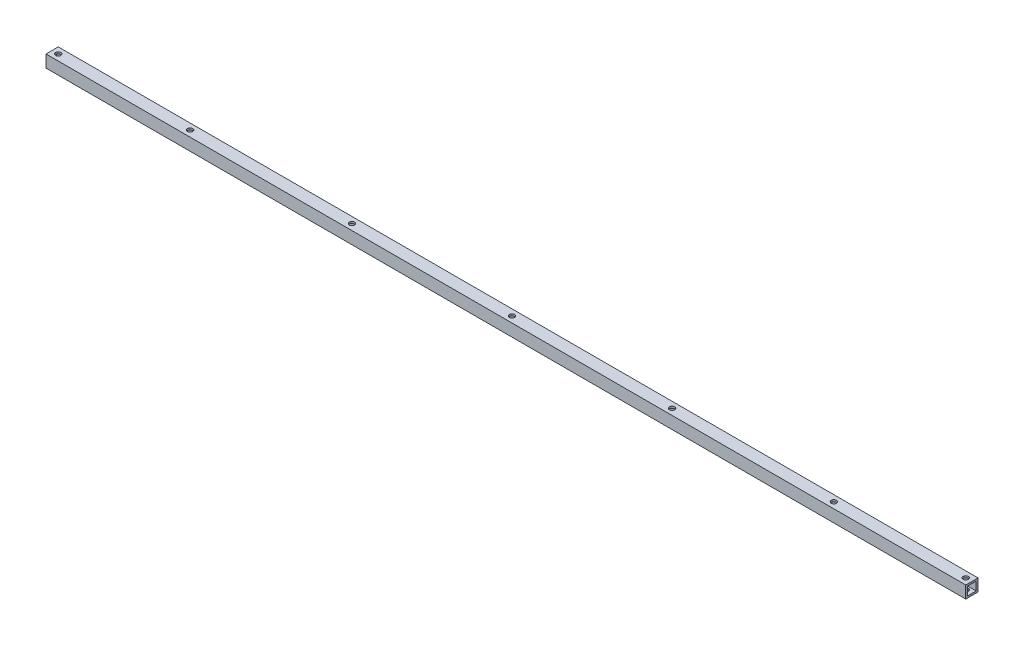
SolidWorks part; units mm, degrees
material "5052-H34"
ref_plane "正面" through (0, 0, 0) normal (0, 0, 1) x (1, 0, 0)
ref_plane "平面" through (0, 0, 0) normal (0, 1, 0) x (1, 0, 0)
ref_plane "右側面" through (0, 0, 0) normal (1, 0, 0) x (0, 0, -1)
sketch "ｽｹｯﾁ1" plane through (0, 0, 0) normal (1, 0, 0) x (0, 0, -1)
  line L1 (-5, 5) -> (5, 5)
  line L2 (-5, 5) -> (-5, -5)
  line L3 (-5, -5) -> (5, -5)
  line L4 (5, 5) -> (5, -5)
  line L5 (-5, 5) -> (5, -5) construction
  line L6 (-5, -5) -> (5, 5) construction
  point P0 (0, 0)
  dimension "D1" = 10
  dimension "D2" = 10
extrude "押し出し-薄板1" add sketch "ｽｹｯﾁ1" along normal blind 750 thin
sketch "ｽｹｯﾁ2" plane through (0, 5, 0) normal (0, 1, 0) x (1, 0, 0)
  line L0 (750, 0) -> (745, 0) construction
  line L1 (750, 5) -> (750, -5) construction
  line L2 (0, 0) -> (5, 0) construction
  line L3 (375, 5) -> (375, -5) construction
  line L4 (745, 0) -> (505.5, 0) construction
  line L5 (750, 5) -> (0, 5) construction
  line L6 (750, -5) -> (0, -5) construction
  circle A0 centre (745, 0) radius 2.15
  circle A1 centre (5, 0) radius 2.15
  circle A3 centre (505.5, 0) radius 2.15
  circle A4 centre (244.5, 0) radius 2.15
  circle A5 centre (637.5, 0) radius 2.15
  circle A6 centre (112.5, 0) radius 2.15
  circle A7 centre (375, 0) radius 2.15
  dimension "D3" = 4.3
  dimension "D4" = 244.5
  dimension "D7" = 4.3
  dimension "D5" = 112.5
  dimension "D1" = 5
  dimension "D2" = 5
extrude "ｶｯﾄ - 押し出し1" cut sketch "ｽｹｯﾁ2" against normal through all
